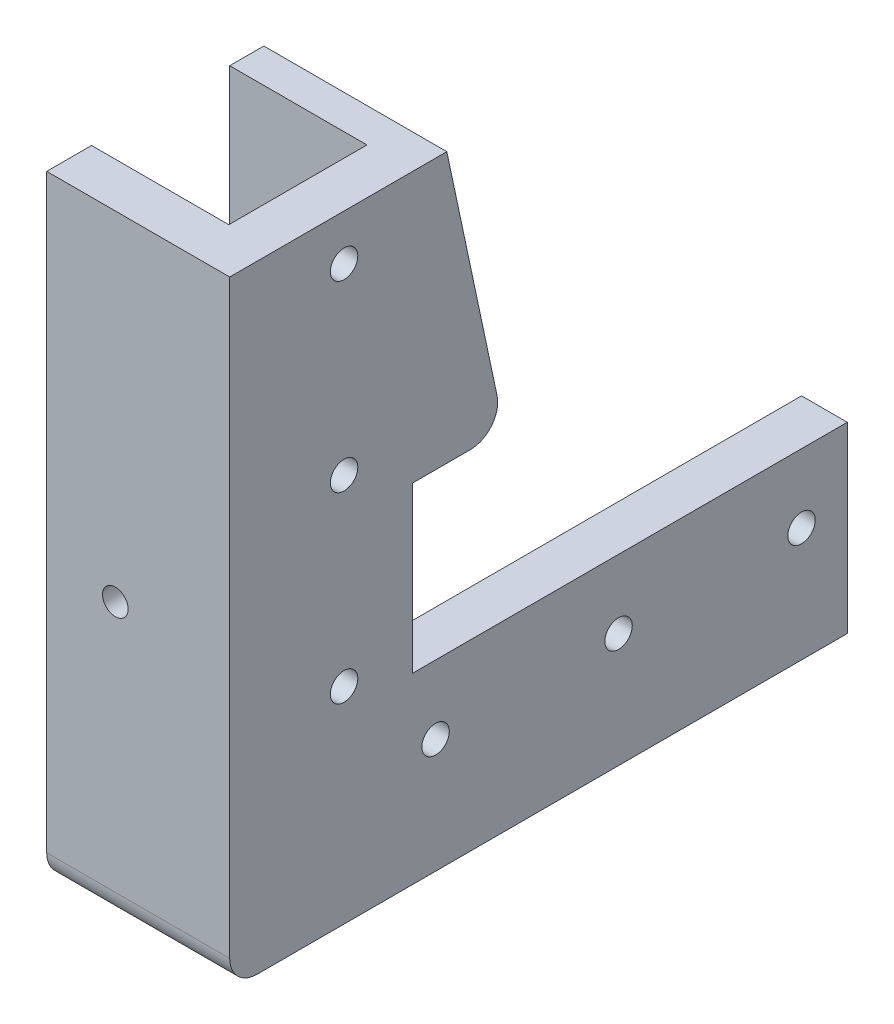
SolidWorks part; units mm, degrees
material "PLA"
ref_plane "前视基准面" through (0, 0, 0) normal (0, 0, 1) x (1, 0, 0)
ref_plane "上视基准面" through (0, 0, 0) normal (0, 1, 0) x (1, 0, 0)
ref_plane "右视基准面" through (0, 0, 0) normal (1, 0, 0) x (0, 0, -1)
sketch "草图1" plane through (0, 0, 0) normal (1, 0, 0) x (0, 0, -1)
  line L0 (0, 0) -> (0, 55) construction
  line L1 (0, 0) -> (55, 0) construction
  line L2 (7.5, 7.5) -> (55, 7.5) construction
  line L3 (7.5, 7.5) -> (7.5, 55) construction
  line L4 (-7.5, -7.5) -> (55, -7.5) construction
  line L5 (-7.5, -7.5) -> (-7.5, 55) construction
  line L6 (-12.5, -12.5) -> (55, -12.5)
  line L7 (-12.5, -12.5) -> (-12.5, 55)
  line L8 (55, 7.5) -> (7.5, 7.5)
  line L9 (7.5, 7.5) -> (7.5, 25.5)
  line L10 (7.5, 25.5) -> (17.5, 25.5)
  line L11 (17.5, 25.5) -> (11.2296, 55)
  line L12 (11.2296, 55) -> (-12.5, 55)
  line L13 (55, -12.5) -> (55, 7.5)
  line L14 (-7.5, -7.5) -> (0, 0) construction
  circle A0 centre (0, 10) radius 1.5
  circle A1 centre (0, 30) radius 1.5
  circle A2 centre (10, 0) radius 1.5
  circle A3 centre (30, 0) radius 1.5
  circle A4 centre (50, 0) radius 1.5
  circle A5 centre (0, 50) radius 1.5
  dimension "D8" = 20
  dimension "D9" = 10
  dimension "D10" = 20
  dimension "D11" = 3
  dimension "D4" = 18
  dimension "D5" = 10
  dimension "D6" = 55
  dimension "D7" = 55
  dimension "D12" = 12
  dimension "D1" = 7.5
  dimension "D2" = 7.5
  dimension "D3" = 5
extrude "凸台-拉伸1" add sketch "草图1" along normal blind 20
sketch "草图2" plane through (0, 0, 0) normal (-1, 0, 0) x (0, 0, 1)
  line L0 (7.6, 55) -> (7.6, -7.6)
  line L1 (-11.2296, 55) -> (12.5, 55) construction
  line L2 (7.6, -7.6) -> (-55, -7.6)
  line L3 (-55, -12.5) -> (-55, 7.5) construction
  line L4 (-55, -7.6) -> (-55, 7.5)
  line L5 (-55, 7.5) -> (-7.5, 7.5)
  line L6 (-7.5, 7.5) -> (-7.5, 55)
  line L7 (-7.5, 55) -> (7.6, 55)
  dimension "D1" = 15.1
  dimension "D2" = 15.1
extrude "切除-拉伸1" cut sketch "草图2" against normal blind 15
sketch "草图3" plane through (0, 0, 7.6) normal (0, 0, -1) x (-1, 0, 0)
  line L0 (0, -7.6) -> (0, 55) construction
  circle A0 centre (-7.5, 18) radius 1.4
  dimension "D1" = 18
  dimension "D2" = 7.5
  dimension "D3" = 2.8
extrude "切除-拉伸2" cut sketch "草图3" against normal through all
fillet "圆角1" radius 3 2 edges at (10, 25.5, -17.5) (10, -12.5, 12.5)
